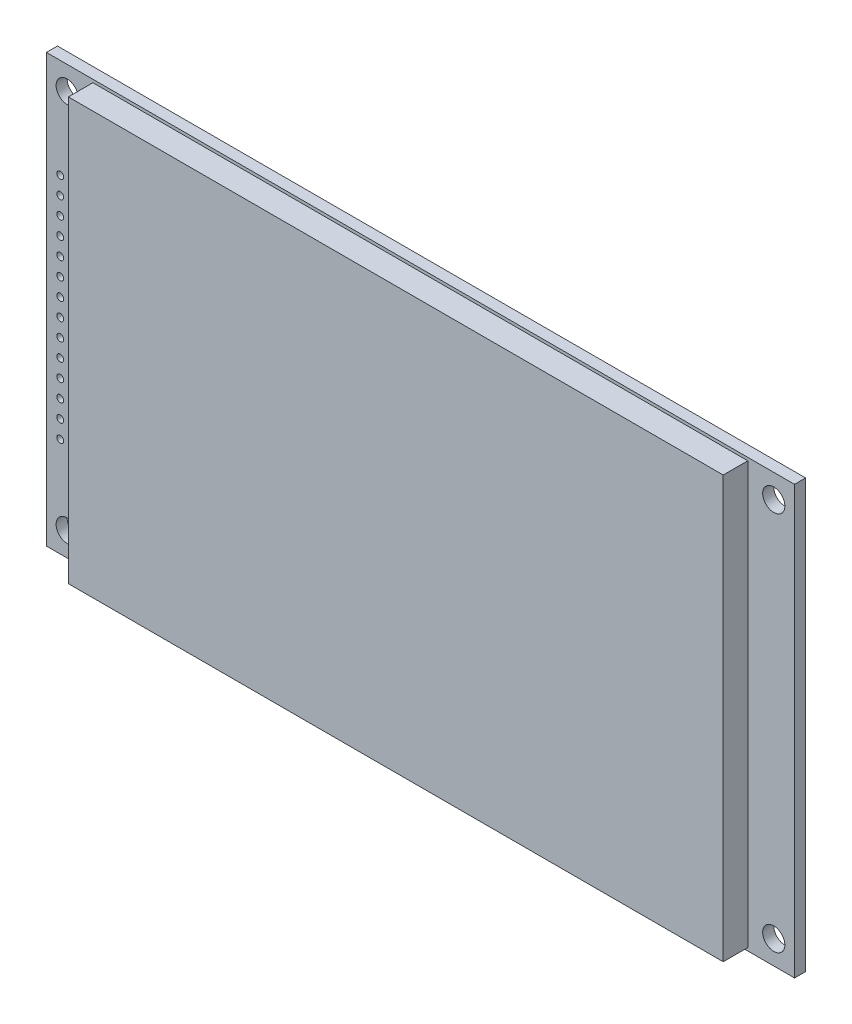
SolidWorks part; units mm, degrees
ref_plane "Front Plane" through (0, 0, 0) normal (0, 0, 1) x (1, 0, 0)
ref_plane "Top Plane" through (0, 0, 0) normal (0, 1, 0) x (1, 0, 0)
ref_plane "Right Plane" through (0, 0, 0) normal (1, 0, 0) x (0, 0, -1)
sketch "Sketch1" plane through (0, 0, 0) normal (0, 0, 1) x (1, 0, 0)
  line L1 (-54.02, 30.87) -> (54.02, 30.87)
  line L2 (-54.02, 30.87) -> (-54.02, -30.87)
  line L3 (-54.02, -30.87) -> (54.02, -30.87)
  line L4 (54.02, 30.87) -> (54.02, -30.87)
  line L5 (-54.02, 30.87) -> (54.02, -30.87) construction
  line L6 (-54.02, -30.87) -> (54.02, 30.87) construction
  circle A0 centre (-51.02, 27.45) radius 1.6
  circle A1 centre (-51.02, -27.45) radius 1.6
  circle A2 centre (51.02, -27.45) radius 1.6
  circle A3 centre (51.02, 27.45) radius 1.6
  point P0 (0, 0)
  dimension "D5" = 3.2
  dimension "D6" = 3.2
  dimension "D9" = 3.2
  dimension "D1" = 61.74
  dimension "D2" = 108.04
  dimension "D3" = 3.42
  dimension "D4" = 3
  dimension "D7" = 3
  dimension "D8" = 3.42
  dimension "D10" = 3
  dimension "D11" = 3.42
  dimension "D12" = 3
  dimension "D13" = 3.42
extrude "Boss-Extrude1" add sketch "Sketch1" along normal blind 1.6
sketch "Sketch2" plane through (0, 0, 1.6) normal (0, 0, 1) x (1, 0, 0)
  line L0 (-47.3, 0) -> (47.27, 0) construction
  line L1 (47.27, 30.44) -> (-47.3, 30.44)
  line L2 (47.27, 30.44) -> (47.27, -30.44)
  line L3 (47.27, -30.44) -> (-47.3, -30.44)
  line L4 (-47.3, 30.44) -> (-47.3, -30.44)
  line L5 (-54.02, 30.87) -> (-54.02, -30.87) construction
  dimension "D1" = 94.57
  dimension "D2" = 60.88
  dimension "D3" = 6.75
  dimension "D4" = 6.72
extrude "Boss-Extrude2" add sketch "Sketch2" along normal blind 3.55
sketch "Sketch3" plane through (0, 0, 1.6) normal (0, 0, 1) x (1, 0, 0)
  line L0 (54.02, 30.87) -> (-54.02, 30.87) construction
  circle A0 centre (-52.02, 16.51) radius 0.5
  circle A1 centre (-52.02, 13.97) radius 0.5
  circle A2 centre (-52.02, 11.43) radius 0.5
  circle A3 centre (-52.02, 8.89) radius 0.5
  circle A4 centre (-52.02, 6.35) radius 0.5
  circle A5 centre (-52.02, 3.81) radius 0.5
  circle A6 centre (-52.02, 1.27) radius 0.5
  circle A7 centre (-52.02, -1.27) radius 0.5
  circle A8 centre (-52.02, -3.81) radius 0.5
  circle A9 centre (-52.02, -6.35) radius 0.5
  circle A10 centre (-52.02, -8.89) radius 0.5
  circle A11 centre (-52.02, -11.43) radius 0.5
  circle A12 centre (-52.02, -13.97) radius 0.5
  circle A13 centre (-52.02, -16.51) radius 0.5
  dimension "D3" = 1
  dimension "D1" = 14.36
  dimension "D2" = 2
  dimension "D4" = 14
extrude "Cut-Extrude1" cut sketch "Sketch3" against normal blind 3.55
